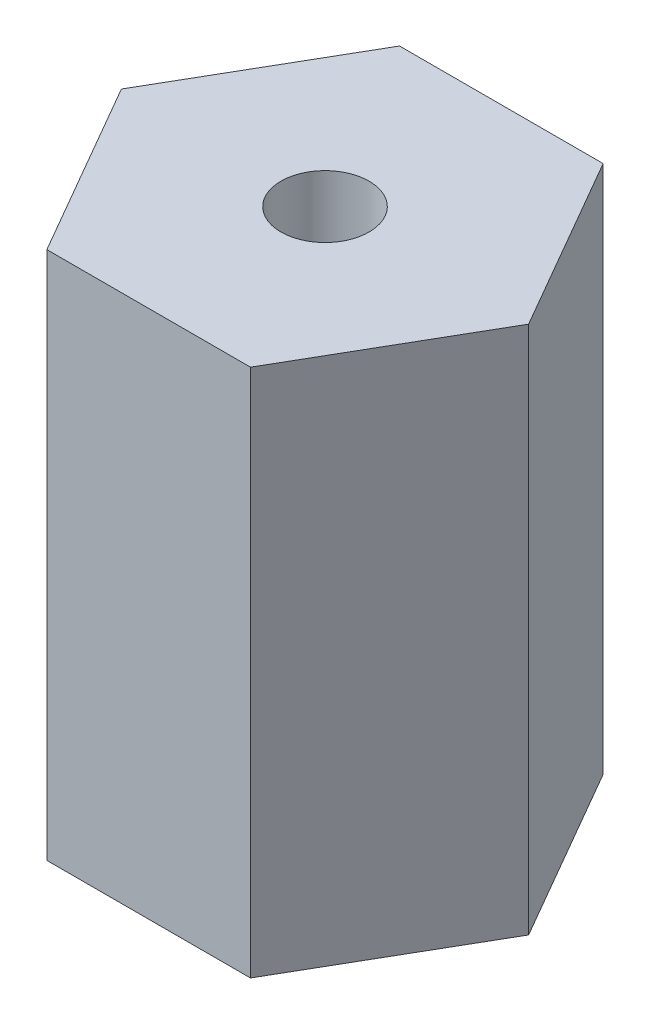
SolidWorks part; units mm, degrees
ref_plane "Front Plane" through (0, 0, 0) normal (0, 0, 1) x (1, 0, 0)
ref_plane "Top Plane" through (0, 0, 0) normal (0, 1, 0) x (1, 0, 0)
ref_plane "Right Plane" through (0, 0, 0) normal (1, 0, 0) x (0, 0, -1)
sketch "Sketch1" plane through (0, 0, 0) normal (0, 1, 0) x (1, 0, 0)
  line L1 (-3.3632, 5.8253) -> (-9.1368, 15.8253)
  line L2 (-9.1368, 15.8253) -> (-20.6838, 15.8253)
  line L3 (-20.6838, 15.8253) -> (-26.4573, 5.8253)
  line L4 (-26.4573, 5.8253) -> (-20.6838, -4.1747)
  line L5 (-20.6838, -4.1747) -> (-9.1368, -4.1747)
  line L6 (-9.1368, -4.1747) -> (-3.3632, 5.8253)
  circle A0 centre (-14.9103, 5.8253) radius 10 construction
  circle A1 centre (-14.9103, 5.8253) radius 2.5
  dimension "D1" = 20
  dimension "D2" = 5
extrude "Boss-Extrude1" add sketch "Sketch1" along normal blind 30
